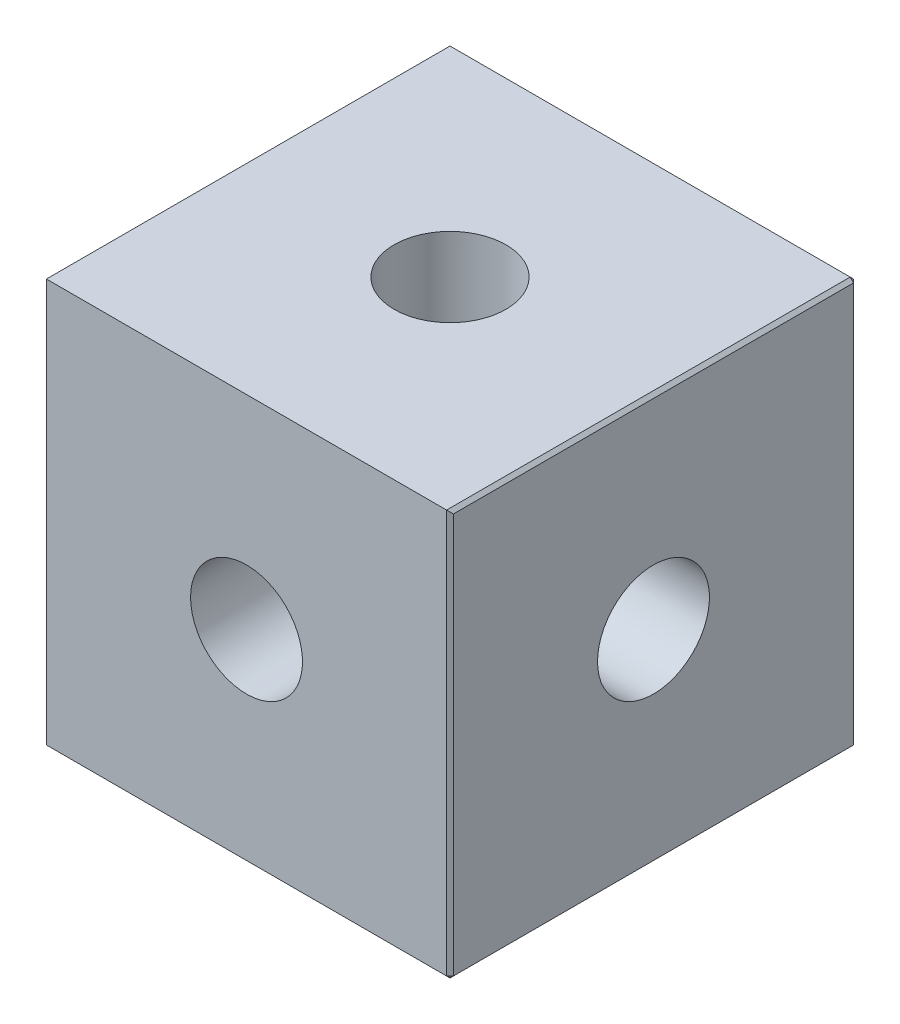
SolidWorks part; units mm, degrees
ref_plane "Front Plane" through (0, 0, 0) normal (0, 0, 1) x (1, 0, 0)
ref_plane "Top Plane" through (0, 0, 0) normal (0, 1, 0) x (1, 0, 0)
ref_plane "Right Plane" through (0, 0, 0) normal (1, 0, 0) x (0, 0, -1)
other "Configuration Table"
sketch "草图1" plane through (0, 0, 0) normal (0, 1, 0) x (1, 0, 0)
  line L1 (-6, 6) -> (6, 6)
  line L2 (-6, 6) -> (-6, -6)
  line L3 (-6, -6) -> (6, -6)
  line L4 (6, 6) -> (6, -6)
  line L5 (-6, 6) -> (6, -6) construction
  line L6 (-6, -6) -> (6, 6) construction
  point P0 (0, 0)
extrude "凸台-拉伸1" add sketch "草图1" along normal blind 12
sketch "草图6" plane through (0, 12, 0) normal (0, 1, 0) x (1, 0, 0)
  point P0 (0, 0)
hole_wizard "M4x0.7 螺纹孔1" positions "草图6" profile "草图5" tap size "M4x0.7" standard "ANSI Metric" end condition through all
sketch "草图5" plane through (0, 12, 0) normal (1, 0, 0) x (0, 0, 1)
  line L0 (0, 0) -> (0, 12)
  line L1 (0, 12) -> (1.65, 12)
  line L2 (1.65, 12) -> (1.65, 0)
  line L5 (1.65, 0) -> (0, 0)
  line L11 (0, -6.35) -> (0, 107.95) construction
  dimension "通孔螺纹孔钻头直径" = 3.3
  dimension "通孔螺纹孔钻头深度" = 12
cosmetic thread "孔螺纹线1" parameters "D2"=4
sketch "草图9" plane through (0, 0, -6) normal (0, 0, -1) x (-1, 0, 0)
  line L0 (-6, 6) -> (6, 6) construction
  line L1 (-6, 12) -> (-6, 0) construction
  line L2 (6, 12) -> (6, 0) construction
sketch "草图12" plane through (0, 0, -6) normal (0, 0, -1) x (-1, 0, 0)
  line L0 (-6, 6) -> (6, 6) construction
  point P0 (0, 6)
hole_wizard "M4x0.7 螺纹孔2" positions "草图12" profile "草图11" tap size "M4x0.7" standard "ANSI Metric" end condition through all
sketch "草图11" plane through (0, 6, -6) normal (1, 0, 0) x (0, 1, 0)
  line L0 (0, 0) -> (0, 12)
  line L1 (0, 12) -> (1.65, 12)
  line L2 (1.65, 12) -> (1.65, 0)
  line L5 (1.65, 0) -> (0, 0)
  line L11 (0, -6.35) -> (0, 107.95) construction
  dimension "通孔螺纹孔钻头直径" = 3.3
  dimension "通孔螺纹孔钻头深度" = 12
cosmetic thread "孔螺纹线2" parameters "D2"=4
sketch "草图13" plane through (-6, 0, 0) normal (-1, 0, 0) x (0, 0, 1)
  line L0 (-6, 6) -> (6, 6) construction
  line L1 (-6, 12) -> (-6, 0) construction
  line L2 (6, 12) -> (6, 0) construction
sketch "草图16" plane through (-6, 0, 0) normal (-1, 0, 0) x (0, 0, 1)
  line L0 (-6, 6) -> (6, 6) construction
  point P0 (0, 6)
hole_wizard "M4x0.7 螺纹孔3" positions "草图16" profile "草图15" tap size "M4x0.7" standard "ANSI Metric" end condition through all
sketch "草图15" plane through (-6, 6, 0) normal (0, 1, 0) x (0, 0, 1)
  line L0 (0, 0) -> (0, 12)
  line L1 (0, 12) -> (1.65, 12)
  line L2 (1.65, 12) -> (1.65, 0)
  line L5 (1.65, 0) -> (0, 0)
  line L11 (0, -6.35) -> (0, 107.95) construction
  dimension "通孔螺纹孔钻头直径" = 3.3
  dimension "通孔螺纹孔钻头深度" = 12
cosmetic thread "孔螺纹线3" parameters "D2"=4
chamfer "倒角1" distance 0.1 angle 45 11 edges at (6, 12, 0) (0, 12, -6) (6, 6, -6) (0, 0, -6) (6, 0, 0) (6, 6, 6) (0, 0, 6) (-6, 0, 0) (-6, 6, 6) (-6, 12, 0) (-6, 6, -6)
